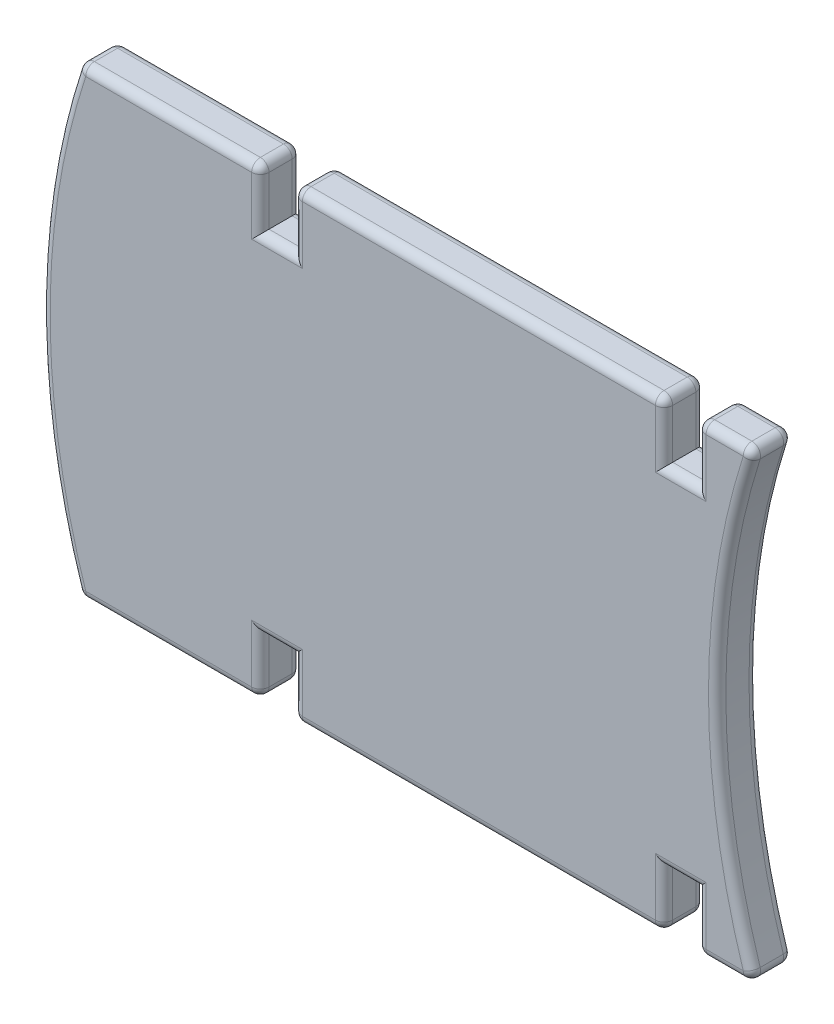
SolidWorks part; units mm, degrees
ref_plane "Plan de face" through (0, 0, 0) normal (0, 0, 1) x (1, 0, 0)
ref_plane "Plan de dessus" through (0, 0, 0) normal (0, 1, 0) x (1, 0, 0)
ref_plane "Plan de droite" through (0, 0, 0) normal (1, 0, 0) x (0, 0, -1)
sketch "Esquisse1" plane through (0, 0, 0) normal (0, 0, 1) x (1, 0, 0)
  line L0 (-47.3709, 16) -> (-34.8709, 16)
  line L1 (-34.8709, 16) -> (-34.8709, 12)
  line L2 (-34.8709, 12) -> (-32.5709, 12)
  line L3 (-32.5709, 12) -> (-32.5709, 16)
  line L4 (-32.5709, 16) -> (-6.9709, 16)
  line L5 (-6.9709, 16) -> (-6.9709, 12)
  line L6 (-6.9709, 12) -> (-4.6709, 12)
  line L7 (-4.6709, 12) -> (-4.6709, 16)
  line L8 (-4.6709, 16) -> (-0.6709, 16)
  line L9 (30.2564, 0) -> (-23.4807, 0) construction
  line L10 (-4.6709, -16) -> (-0.6709, -16)
  line L11 (-4.6709, -12) -> (-4.6709, -16)
  line L12 (-6.9709, -12) -> (-4.6709, -12)
  line L13 (-6.9709, -16) -> (-6.9709, -12)
  line L14 (-32.5709, -16) -> (-6.9709, -16)
  line L15 (-32.5709, -12) -> (-32.5709, -16)
  line L16 (-34.8709, -12) -> (-32.5709, -12)
  line L17 (-34.8709, -16) -> (-34.8709, -12)
  line L18 (-47.3709, -16) -> (-34.8709, -16)
  arc A0 (-47.3709, 16) -> (-47.3709, -16) centre (0, 0) ccw
  arc A1 (-0.6709, 16) -> (-0.6709, -16) centre (46.7, 0) ccw
  dimension "D1" = 4
  dimension "D8" = 4
  dimension "D7" = 50
  dimension "D2" = 12.5
  dimension "D3" = 25.6
  dimension "D4" = 2.3
  dimension "D5" = 2.3
  dimension "D6" = 16
extrude "Boss.-Extru.1" add sketch "Esquisse1" along normal blind 2.8
fillet "Congé1" radius 0.6 52 edges at (-34.8709, 16, 1.4) (-6.9709, 16, 1.4) (-32.5709, 16, 1.4) (-0.6709, 16, 1.4) (-4.6709, 16, 1.4) (-4.6709, -16, 1.4) (-0.6709, -16, 1.4) (-32.5709, -16, 1.4) (-6.9709, -16, 1.4) (-47.3709, 16, 1.4) (-47.3709, -16, 1.4) (-34.8709, -16, 1.4) (-41.1209, -16, 0) (-34.8709, -14, 0) (-33.7209, -12, 0) (-32.5709, -14, 0) (-19.7709, -16, 0) (-6.9709, -14, 0) (-5.8209, -12, 0) (-4.6709, -14, 0) (-2.6709, -16, 0) (-3.3, 0, 0) (-2.6709, 16, 0) (-4.6709, 14, 0) (-5.8209, 12, 0) (-6.9709, 14, 0) (-19.7709, 16, 0) (-32.5709, 14, 0) (-33.7209, 12, 0) (-34.8709, 14, 0) (-41.1209, 16, 0) (-50, 0, 0) (-41.1209, 16, 2.8) (-34.8709, 14, 2.8) (-33.7209, 12, 2.8) (-32.5709, 14, 2.8) (-19.7709, 16, 2.8) (-6.9709, 14, 2.8) (-5.8209, 12, 2.8) (-4.6709, 14, 2.8) (-2.6709, 16, 2.8) (-3.3, 0, 2.8) (-2.6709, -16, 2.8) (-4.6709, -14, 2.8) (-5.8209, -12, 2.8) (-6.9709, -14, 2.8) (-19.7709, -16, 2.8) (-32.5709, -14, 2.8) (-33.7209, -12, 2.8) (-34.8709, -14, 2.8) (-41.1209, -16, 2.8) (-50, 0, 2.8)
